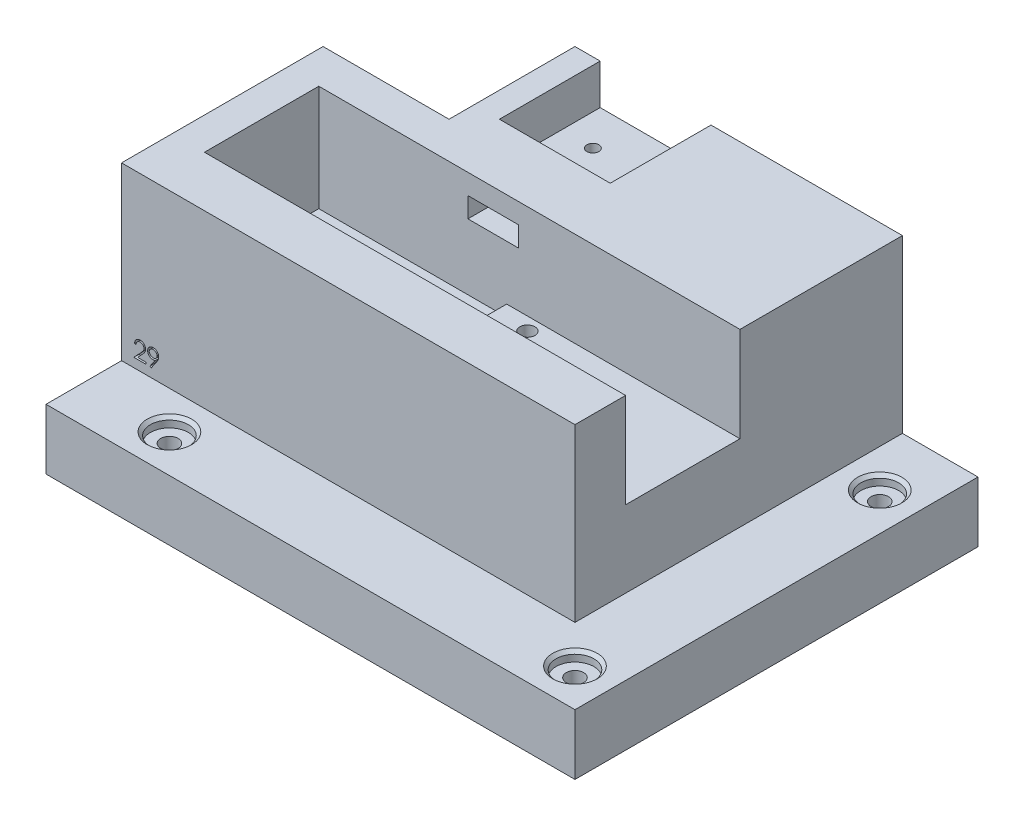
SolidWorks part; units mm, degrees
ref_plane "Front Plane" through (0, 0, 0) normal (0, 0, 1) x (1, 0, 0)
ref_plane "Top Plane" through (0, 0, 0) normal (0, 1, 0) x (1, 0, 0)
ref_plane "Right Plane" through (0, 0, 0) normal (1, 0, 0) x (0, 0, -1)
sketch "Sketch1" plane through (0, 0, 0) normal (0, 1, 0) x (1, 0, 0)
  line L1 (0, 0) -> (85, 0)
  line L2 (0, 0) -> (0, -65)
  line L3 (0, -65) -> (85, -65)
  line L4 (85, 0) -> (85, -65)
  dimension "D1" = 85
  dimension "D2" = 65
extrude "Boss-Extrude1" add sketch "Sketch1" along normal blind 46
sketch "Sketch2" plane through (0, 46, 0) normal (0, 1, 0) x (1, 0, 0)
  line L1 (0, 0) -> (20, 0)
  line L2 (0, 0) -> (0, -25)
  line L3 (0, -25) -> (20, -25)
  line L4 (20, 0) -> (20, -25)
  dimension "D1" = 25
  dimension "D2" = 20
extrude "Cut-Extrude1" cut sketch "Sketch2" against normal blind 46
sketch "Sketch3" plane through (20, 0, 0) normal (-1, 0, 0) x (0, 0, 1)
  line L1 (0, 0) -> (0, 46) construction
  line L2 (25, 46) -> (0, 46) construction
  circle A0 centre (12.5, 35) radius 3.15
  dimension "D3" = 6.3
  dimension "D1" = 12.5
  dimension "D2" = 11
extrude "Cut-Extrude2" cut sketch "Sketch3" against normal blind 10
sketch "Sketch4" plane through (0, 0, 0) normal (0, 0, -1) x (-1, 0, 0)
  line L0 (-85, 46) -> (-20, 46) construction
  line L1 (-85, 46) -> (-85, 0) construction
  circle A0 centre (-65, 35) radius 3.15
  dimension "D1" = 6.3
  dimension "D2" = 11
  dimension "D3" = 20
extrude "Cut-Extrude3" cut sketch "Sketch4" against normal blind 20
sketch "Sketch5" plane through (85, 0, 0) normal (1, 0, 0) x (0, 0, -1)
  line L0 (-65, 12) -> (0, 12) construction
  line L1 (-65, 46) -> (-65, 0) construction
  line L2 (0, 46) -> (0, 0) construction
  line L3 (-65, 0) -> (0, 0) construction
  line L5 (0, 0) -> (-65, 0)
  line L6 (0, 0) -> (0, 12)
  line L7 (0, 12) -> (-65, 12)
  line L8 (-65, 0) -> (-65, 12)
  dimension "D1" = 12
extrude "Boss-Extrude2" add sketch "Sketch5" along normal blind 15
sketch "Sketch6" plane through (0, 0, 65) normal (0, 0, 1) x (1, 0, 0)
  line L0 (100, 12) -> (0, 12) construction
  line L1 (0, 46) -> (0, 0) construction
  line L3 (100, 0) -> (0, 0)
  line L4 (100, 0) -> (100, 12)
  line L5 (100, 12) -> (0, 12)
  line L6 (0, 0) -> (0, 12)
extrude "Boss-Extrude3" add sketch "Sketch6" along normal blind 15
sketch "Sketch7" plane through (0, 0, 0) normal (0, -1, 0) x (1, 0, 0)
  line L0 (0, 25) -> (0, 80) construction
  line L1 (1.4, 32.25) -> (83.6, 32.25)
  line L2 (1.4, 32.25) -> (1.4, 54.95)
  line L3 (1.4, 54.95) -> (83.6, 54.95)
  line L4 (83.6, 32.25) -> (83.6, 54.95)
  line L5 (100, 0) -> (20, 0) construction
  dimension "D1" = 22.7
  dimension "D2" = 82.2
  dimension "D3" = 1.4
  dimension "D4" = 32.25
extrude "Cut-Extrude4" cut sketch "Sketch7" against normal blind 43.2
sketch "Sketch9" plane through (0, 43.2, 0) normal (0, -1, 0) x (1, 0, 0)
  line L0 (83.6, 32.25) -> (83.6, 54.95) construction
  line L1 (65.9, 44.6969) -> (53.6, 44.6969) construction
  line L2 (53.6, 44.6969) -> (45.3, 44.6969) construction
  line L3 (45.3, 44.6969) -> (45.3, 35.9469) construction
  line L4 (45.3, 44.6969) -> (45.3, 53.4469) construction
  circle A0 centre (65.9, 44.6969) radius 3.25
  circle A1 centre (53.6, 44.6969) radius 2.35
  circle A2 centre (45.3, 53.4469) radius 1.5
  circle A3 centre (45.3, 35.9469) radius 1.5
  dimension "D2" = 6.5
  dimension "D4" = 4.7
  dimension "D8" = 3
  dimension "D9" = 3
  dimension "D1" = 17.7
  dimension "D3" = 12.3
  dimension "D5" = 8.3
  dimension "D6" = 8.75
  dimension "D7" = 8.75
extrude "Cut-Extrude5" cut sketch "Sketch9" against normal blind 43.2
sketch "Sketch10" plane through (0, 43.2, 0) normal (0, -1, 0) x (1, 0, 0)
  line L0 (83.6, 54.95) -> (1.4, 54.95) construction
  line L4 (38.6, 32.25) -> (38.6, 54.95)
  line L5 (38.6, 54.95) -> (1.4, 54.95)
  line L6 (1.4, 54.95) -> (1.4, 32.25)
  line L7 (1.4, 32.25) -> (38.6, 32.25)
extrude "Cut-Extrude6" cut sketch "Sketch10" against normal blind 2.25
sketch "Sketch11" plane through (0, 45.45, 0) normal (0, -1, 0) x (1, 0, 0)
  line L0 (38.6, 54.95) -> (38.6, 32.25) construction
  line L1 (38.6, 43.6) -> (34.33, 43.6) construction
  line L2 (34.33, 43.6) -> (34.33, 40.1) construction
  line L3 (34.33, 40.1) -> (29.53, 40.1) construction
  line L4 (29.53, 40.1) -> (29.53, 47.1) construction
  line L5 (29.53, 47.1) -> (34.33, 47.1) construction
  line L6 (34.33, 47.1) -> (34.33, 43.6) construction
  line L7 (29.53, 47.1) -> (29.53, 40.1)
  line L8 (29.53, 40.1) -> (34.33, 40.1)
  line L9 (34.33, 40.1) -> (34.33, 47.1)
  line L10 (34.33, 47.1) -> (29.53, 47.1)
  dimension "D1" = 4.27
  dimension "D2" = 4.8
  dimension "D3" = 3.5
  dimension "D4" = 3.5
extrude "Cut-Extrude7" cut sketch "Sketch11" against normal blind 2.25
sketch "Sketch12" plane through (0, 12, 0) normal (0, 1, 0) x (1, 0, 0)
  line L0 (85, -65) -> (100, -80) construction
  line L1 (0, -80) -> (0, -65) construction
  line L2 (100, 0) -> (85, 0) construction
  circle A0 centre (92.5, -72.5) radius 3.25
  circle A1 centre (12, -72.5) radius 3.25
  circle A2 centre (92.5, -12) radius 3.25
  dimension "D1" = 6.5
  dimension "D2" = 6.5
  dimension "D3" = 6.5
  dimension "D4" = 12
  dimension "D5" = 12
hole_wizard "CBORE for #5 Binding Head Machine Screw1" positions "Sketch13" profile "Sketch14" counterbore size "#5" standard "ANSI Inch" end condition through all
sketch "Sketch13" plane through (0, 12, 0) normal (0, 1, 0) x (1, 0, 0)
  point P0 (92.5, -12)
  point P3 (92.5, -72.5)
  point P6 (12, -72.5)
sketch "Sketch14" plane through (92.5, 12, 12) normal (1, 0, 0) x (0, 0, 1)
  line L0 (0, 0) -> (0, 12)
  line L1 (0, 12) -> (1.7272, 12)
  line L3 (1.7272, 12) -> (1.7272, 1.9812)
  line L4 (3.7706, 1.9812) -> (1.7272, 1.9812)
  line L5 (3.7706, 1.9812) -> (3.7706, 0.635)
  line L6 (3.7706, 0.635) -> (4.4056, 0)
  line L7 (4.4056, 0) -> (0, 0)
  line L8 (-3.7706, 0.635) -> (-4.4056, 0) construction
  line L11 (0, -6.35) -> (0, 107.95) construction
  dimension "Thru Hole Dia." = 3.4544
  dimension "Thru Hole Depth" = 12
  dimension "C'Bore Dia." = 7.5413
  dimension "C'Bore Depth" = 1.9812
  dimension "Near C'Sink Dia." = 8.8113
  dimension "Near C'Sink Angle" = 90
sketch "Sketch15" plane through (20, 0, 0) normal (-1, 0, 0) x (0, 0, 1)
  circle A0 centre (12.5, 35) radius 3.15
extrude "Boss-Extrude4" add sketch "Sketch15" against normal blind 10
sketch "Sketch16" plane through (83.6, 0, 0) normal (-1, 0, 0) x (0, 0, 1)
  line L1 (32.25, 0) -> (54.95, 0)
  line L2 (32.25, 0) -> (32.25, 43.2)
  line L3 (32.25, 43.2) -> (54.95, 43.2)
  line L4 (54.95, 0) -> (54.95, 43.2)
extrude "Cut-Extrude8" cut sketch "Sketch16" against normal blind 1.5
sketch "Sketch17" plane through (0, 0, 0) normal (0, 0, -1) x (-1, 0, 0)
  line L0 (-85, 46) -> (-20, 46) construction
  line L1 (-47, 46) -> (-25, 46)
  line L2 (-47, 46) -> (-47, 38)
  line L3 (-47, 38) -> (-25, 38)
  line L4 (-25, 46) -> (-25, 38)
  line L5 (-20, 0) -> (-20, 46) construction
  dimension "D1" = 8
  dimension "D2" = 22
  dimension "D3" = 5
extrude "Cut-Extrude9" cut sketch "Sketch17" against normal blind 20
sketch "Sketch18" plane through (0, 38, 0) normal (0, 1, 0) x (1, 0, 0)
  line L0 (47, 0) -> (25, 0) construction
  line L1 (36, -20) -> (36, 0) construction
  line L2 (25, -20) -> (47, -20) construction
  circle A0 centre (31.25, -7.7) radius 1.185
  circle A1 centre (40.75, -7.7) radius 1.185
  dimension "D3" = 2.37
  dimension "D4" = 2.37
  dimension "D1" = 7.7
  dimension "D2" = 7.7
  dimension "D5" = 4.75
  dimension "D6" = 4.75
extrude "Cut-Extrude10" cut sketch "Sketch18" against normal blind 10
sketch "Sketch19" plane through (0, 0, 20) normal (0, 0, -1) x (-1, 0, 0)
  line L0 (-36, 46) -> (-36, 38) construction
  line L1 (-25, 46) -> (-47, 46) construction
  line L2 (-47, 38) -> (-25, 38) construction
  line L3 (-41, 42) -> (-36, 42)
  line L4 (-41, 38) -> (-31, 38)
  line L5 (-41, 38) -> (-41, 42)
  line L7 (-31, 38) -> (-31, 42)
  line L8 (-36, 42) -> (-31, 42)
  dimension "D1" = 5
  dimension "D2" = 5
  dimension "D3" = 4
extrude "Cut-Extrude11" cut sketch "Sketch19" against normal blind 20
sketch "Sketch20" plane through (0, 0, 0) normal (-1, 0, 0) x (0, 0, 1)
  line L0 (25, 46) -> (65, 46)
  line L1 (65, 46) -> (65, 12)
  line L2 (65, 12) -> (80, 12)
  line L3 (80, 12) -> (80, 0)
  line L4 (80, 0) -> (25, 0)
  line L5 (25, 0) -> (25, 46)
extrude "Boss-Extrude5" add sketch "Sketch20" along normal blind 5
sketch "Sketch21" plane through (0, 45.45, 0) normal (0, -1, 0) x (1, 0, 0)
  line L1 (1.4, 54.95) -> (85.1, 54.95)
  line L2 (1.4, 54.95) -> (1.4, 32.25)
  line L3 (1.4, 32.25) -> (85.1, 32.25)
  line L4 (85.1, 54.95) -> (85.1, 32.25)
extrude "Cut-Extrude12" cut sketch "Sketch21" against normal blind 5
sketch "Sketch22" plane through (0, 45.45, 0) normal (0, 1, 0) x (1, 0, 0)
  line L1 (38.6, -32.25) -> (85, -32.25)
  line L2 (38.6, -32.25) -> (38.6, -54.95)
  line L3 (38.6, -54.95) -> (85, -54.95)
  line L4 (85, -32.25) -> (85, -54.95)
extrude "Cut-Extrude13" cut sketch "Sketch22" against normal blind 5
sketch "Sketch23" plane through (0, 0, 0) normal (0, -1, 0) x (1, 0, 0)
  line L1 (1.4, 54.95) -> (85.1, 54.95)
  line L2 (1.4, 54.95) -> (1.4, 32.25)
  line L3 (1.4, 32.25) -> (85.1, 32.25)
  line L4 (85.1, 54.95) -> (85.1, 32.25)
extrude "Boss-Extrude6" add sketch "Sketch23" against normal blind 27.2
sketch "Sketch24" plane through (0, 27.2, 0) normal (0, 1, 0) x (1, 0, 0)
  line L0 (85.1, -43.6) -> (1.4, -43.6) construction
  line L1 (85.1, -32.25) -> (85.1, -54.95) construction
  line L2 (1.4, -32.25) -> (1.4, -54.95) construction
  line L3 (85.1, -32.25) -> (85.1, -54.95) construction
  line L4 (53.7, -43.6) -> (53.7, -30.85) construction
  circle A0 centre (66, -43.6) radius 3.25
  circle A1 centre (53.7, -43.6) radius 2.35
  circle A2 centre (45.4, -34.85) radius 1.5
  circle A3 centre (45.4, -52.35) radius 1.5
  dimension "D1" = 6.5
  dimension "D3" = 4.7
  dimension "D5" = 3
  dimension "D6" = 3
  dimension "D2" = 19.1
  dimension "D4" = 12.3
  dimension "D7" = 8.75
  dimension "D8" = 8.75
  dimension "D9" = 8.3
  dimension "D10" = 8.3
extrude "Cut-Extrude14" cut sketch "Sketch24" against normal blind 27
sketch "Sketch25" plane through (0, 27.2, 0) normal (0, 1, 0) x (1, 0, 0)
  line L0 (38.7, -32.25) -> (38.7, -54.95)
  line L1 (85, -32.25) -> (1.4, -32.25) construction
  line L2 (85, -54.95) -> (1.4, -54.95) construction
  line L3 (85.1, -32.25) -> (85.1, -54.95) construction
  line L4 (38.7, -32.25) -> (1.4, -32.25)
  line L5 (1.4, -32.25) -> (1.4, -54.95)
  line L6 (1.4, -54.95) -> (38.7, -54.95)
  dimension "D1" = 46.4
extrude "Cut-Extrude15" cut sketch "Sketch25" against normal blind 2.25
sketch "Sketch26" plane through (0, 24.95, 0) normal (0, 1, 0) x (1, 0, 0)
  line L0 (38.7, -43.6) -> (1.4, -43.6) construction
  line L1 (38.7, -54.95) -> (38.7, -32.25) construction
  line L2 (1.4, -32.25) -> (1.4, -54.95) construction
  line L3 (34.7, -43.6) -> (34.7, -38.6)
  line L4 (34.7, -38.6) -> (38.7, -38.6)
  line L5 (38.7, -38.6) -> (38.7, -43.6)
  line L6 (38.7, -43.6) -> (38.7, -48.6)
  line L7 (38.7, -54.95) -> (38.7, -32.25) construction
  line L8 (38.7, -48.6) -> (34.7, -48.6)
  line L9 (34.7, -48.6) -> (34.7, -43.6)
  dimension "D1" = 5
  dimension "D2" = 5
  dimension "D3" = 4
extrude "Cut-Extrude16" cut sketch "Sketch26" against normal blind 77.25
sketch "Sketch27" plane through (0, 12, 0) normal (0, 1, 0) x (1, 0, 0)
  line L0 (85, 0) -> (85, -80)
  line L1 (100, -80) -> (-5, -80) construction
  line L2 (85, -80) -> (100, -80)
  line L3 (100, -80) -> (100, 0)
  line L4 (100, 0) -> (85, 0)
extrude "Cut-Extrude17" cut sketch "Sketch27" along normal blind 47
sketch "Sketch28" plane through (0, 0, 0) normal (0, 0, -1) x (-1, 0, 0)
  line L0 (-65, 38.15) -> (-61.15, 38.15)
  line L1 (-61.15, 38.15) -> (-61.15, 31.85)
  line L2 (-61.15, 31.85) -> (-68.15, 31.85)
  line L3 (-68.15, 31.85) -> (-68.15, 38.15)
  line L4 (-68.15, 38.15) -> (-65, 38.15)
  circle A0 centre (-65, 35) radius 3.15 construction
  circle A1 centre (-65, 35) radius 3.15 construction
  dimension "D1" = 7
  dimension "D2" = 6.3
extrude "Cut-Extrude18" cut sketch "Sketch28" against normal blind 20
sketch "Sketch30" plane through (0, 0, 65) normal (0, 0, 1) x (1, 0, 0)
  text T0 "29"
extrude "Cut-Extrude19" cut sketch "Sketch30" against normal blind 1
